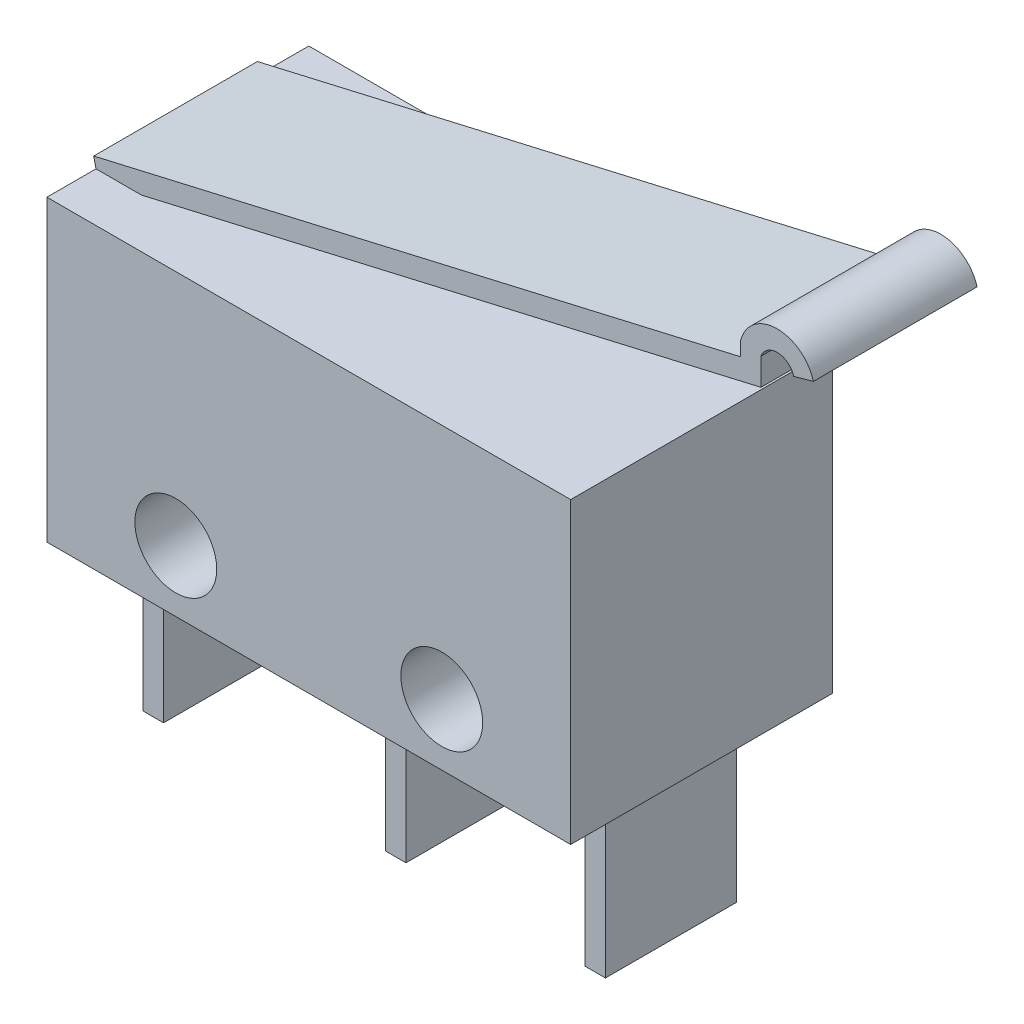
SolidWorks part; units mm, degrees
ref_plane "Спереди" through (0, 0, 0) normal (0, 0, 1) x (1, 0, 0)
ref_plane "Сверху" through (0, 0, 0) normal (0, 1, 0) x (1, 0, 0)
ref_plane "Справа" through (0, 0, 0) normal (1, 0, 0) x (0, 0, -1)
sketch "Эскиз1" plane through (0, 0, 0) normal (0, 0, 1) x (1, 0, 0)
  line L0 (-6.4, 0) -> (-6.4, 7.3) construction
  line L1 (-12.8, 0) -> (0, 0)
  line L2 (-12.8, 0) -> (-12.8, 7.3)
  line L3 (-12.8, 7.3) -> (0, 7.3)
  line L4 (0, 0) -> (0, 7.3)
  line L5 (-9.65, 1.5) -> (-3.15, 1.5) construction
  circle A0 centre (-9.65, 1.5) radius 1
  circle A1 centre (-3.15, 1.5) radius 1
  dimension "D4" = 2
  dimension "D5" = 1.5
  dimension "D1" = 12.8
  dimension "D2" = 7.3
  dimension "D3" = 6.5
extrude "Бобышка-Вытянуть1" add sketch "Эскиз1" along normal mid plane 6.4
sketch "Эскиз2" plane through (0, 0, 0) normal (0, -1, 0) x (1, 0, 0)
  line L0 (-11.8, 1.6) -> (-11.8, -1.6)
  line L1 (-5.8748, 1.6) -> (-5.8748, -1.6)
  line L2 (-1, 1.6) -> (-1, -1.6)
  line L3 (0, 0) -> (-12.8, 0) construction
  line L4 (0, 3.2) -> (0, -3.2) construction
  line L5 (-12.8, 3.2) -> (-12.8, -3.2) construction
  line L6 (-11.8, -1.6) -> (-1, -1.6) construction
  line L7 (-6.4, -1.6) -> (-6.4, 0) construction
  point P12 (-11.8, 0)
  point P13 (-5.8748, 0)
  point P14 (-1, 0)
  dimension "D1" = 3.2
  dimension "D2" = 1
extrude "Вытянуть-Тонкостенный1" add sketch "Эскиз2" along normal blind 4 thin thin type mid plane wall 0.5
sketch "Эскиз3" plane through (0, 0, 0) normal (0, 0, 1) x (1, 0, 0)
  line L0 (-12.8, 7.3) -> (3.2, 11)
  line L1 (3.2, 11) -> (3.2, 11.5)
  line L2 (-12.8, 7.3) -> (-12.8, 0) construction
  line L3 (-12.8, 0) -> (0, 0) construction
  arc A0 (3.2, 11.5) -> (4.4915, 11.5) centre (3.8457, 11.318) cw
  dimension "D1" = 16
  dimension "D2" = 11
  dimension "D3" = 0.5
extrude "Вытянуть-Тонкостенный2" add sketch "Эскиз3" along normal mid plane 4 thin thin type mid plane wall 0.5
